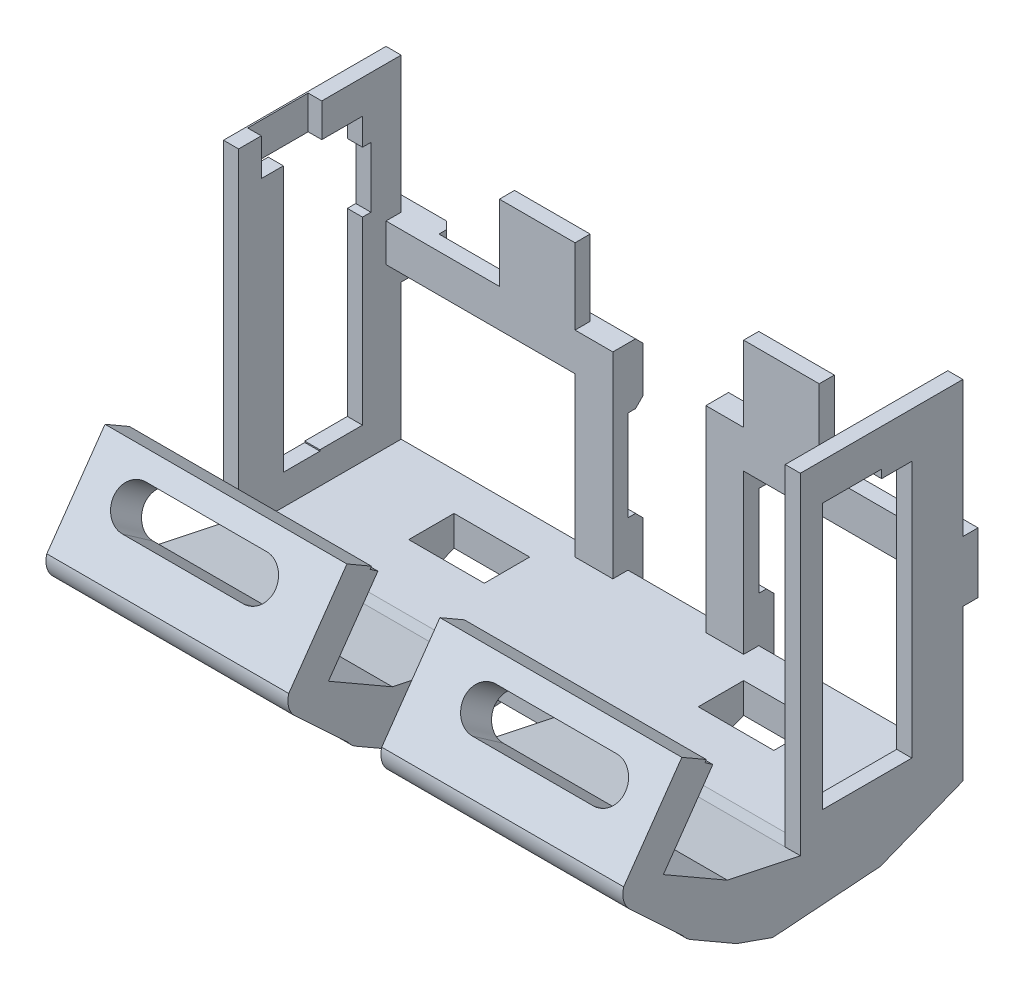
SolidWorks part; units mm, degrees
ref_plane "前视基准面" through (0, 0, 0) normal (0, 0, 1) x (1, 0, 0)
ref_plane "上视基准面" through (0, 0, 0) normal (0, 1, 0) x (1, 0, 0)
ref_plane "右视基准面" through (0, 0, 0) normal (1, 0, 0) x (0, 0, -1)
other "Configuration Table"
sketch "草图5" plane through (0, 0, 0) normal (0, 0, 1) x (1, 0, 0)
  line L0 (-38.15, -23) -> (-38.15, 23)
  line L1 (36.15, -21) -> (-36.15, -21)
  line L2 (36.15, -21) -> (36.15, 23)
  line L4 (-36.15, -21) -> (-36.15, 23)
  line L8 (38.15, -23) -> (38.15, 23)
  line L9 (38.15, -23) -> (-38.15, -23)
  line L10 (36.15, 21) -> (-36.15, 21) construction
  line L11 (38.15, 23) -> (-38.15, 23) construction
  line L12 (-38.15, 23) -> (-36.15, 23)
  line L13 (-36.15, -21) -> (-36.15, 21) construction
  line L14 (36.15, -21) -> (36.15, 21) construction
  line L15 (36.15, 23) -> (38.15, 23)
  point P0 (0, 0)
  dimension "D1" = 72.3
  dimension "D2" = 44
  dimension "D4" = 21
  dimension "D5" = 36.15
  dimension "D3" = 2
extrude "凸台-拉伸2" add sketch "草图5" along normal blind 10
sketch "草图6" plane through (0, 0, 0) normal (0, 0, -1) x (-1, 0, 0)
  line L0 (-38.15, -23) -> (-38.15, 23) construction
  line L1 (-36.15, 5) -> (-6.15, 5)
  line L2 (-38.15, 5) -> (-38.15, 0)
  line L3 (-36.15, 0) -> (-11.15, 0)
  line L5 (38.15, -23) -> (-38.15, -23) construction
  line L7 (-11.15, 0) -> (-11.15, -21)
  line L8 (-11.15, -23) -> (-6.15, -23)
  line L9 (-6.15, 5) -> (-6.15, -21)
  line L10 (38.15, 23) -> (38.15, -23) construction
  line L12 (6.15, 5) -> (6.15, -21)
  line L13 (11.15, 0) -> (36.15, 0)
  line L14 (38.15, 5) -> (38.15, 0)
  line L15 (36.15, -21) -> (36.15, 23) construction
  line L17 (6.15, 5) -> (6.15, 0)
  line L18 (6.15, -23) -> (11.15, -23)
  line L19 (11.15, 0) -> (11.15, -21)
  line L20 (-36.15, 23) -> (-36.15, -21) construction
  line L21 (6.15, 5) -> (38.15, 5)
  line L22 (-36.15, 5) -> (-36.15, 23)
  line L23 (-11.15, -21) -> (-36.15, -21)
  line L24 (6.15, -21) -> (-6.15, -21)
  line L25 (36.15, 0) -> (36.15, -21)
  line L30 (-36.15, -21) -> (-36.15, 23)
  line L31 (-36.15, 23) -> (-38.15, 23)
  line L32 (-38.15, 23) -> (-38.15, -23)
  line L33 (-38.15, -23) -> (38.15, -23)
  line L34 (38.15, -23) -> (38.15, 23)
  line L35 (38.15, 23) -> (36.15, 23)
  line L36 (36.15, 23) -> (36.15, -21)
  line L37 (36.15, -21) -> (-36.15, -21)
  line L38 (-36.15, -21) -> (-36.15, 0)
  line L39 (-36.15, 23) -> (-38.15, 23)
  line L40 (-38.15, 23) -> (-38.15, -23)
  line L41 (-38.15, -23) -> (38.15, -23)
  line L42 (38.15, -23) -> (38.15, 23)
  line L43 (38.15, 23) -> (36.15, 23)
  line L44 (36.15, 23) -> (36.15, 5)
  line L45 (36.15, -21) -> (11.15, -21)
  line M20 (-36.15, -21) -> (-36.15, 23)
  line M21 (-36.15, 23) -> (-38.15, 23)
  line M22 (-38.15, 23) -> (-38.15, -23)
  line M23 (-38.15, -23) -> (38.15, -23)
  line M24 (38.15, -23) -> (38.15, 23)
  line M25 (38.15, 23) -> (36.15, 23)
  line M26 (36.15, 23) -> (36.15, -21)
  line M27 (36.15, -21) -> (-36.15, -21)
  dimension "D1" = 5
  dimension "D2" = 30
  dimension "D3" = 30
  dimension "D4" = 5
  dimension "D5" = 5
  dimension "D7" = 21
  dimension "D6" = 0
extrude "凸台-拉伸3" add sketch "草图6" along normal blind 2 contours L9 L1 L3 L7 M20 M27 | L21 M26 M27 M20 M21 M22 M23 M24 | L21 L12 L19 L13 M27 M26 | L21 M26 M24 M25
sketch "草图7" plane through (0, 0, 10) normal (0, 0, 1) x (1, 0, 0)
  line L8 (36.15, 23) -> (36.15, -21)
  line L9 (36.15, -21) -> (-36.15, -21)
  line L10 (-36.15, -21) -> (-36.15, 23)
  line L11 (-36.15, 23) -> (-38.15, 23)
  line L12 (-38.15, 23) -> (-38.15, -23)
  line L13 (-38.15, -23) -> (38.15, -23)
  line L14 (38.15, -23) -> (38.15, 23)
  line L15 (38.15, 23) -> (36.15, 23)
  line L16 (36.15, 23) -> (36.15, -21)
  line L17 (36.15, -21) -> (-36.15, -21)
  line L18 (-36.15, -21) -> (-36.15, 23)
  line L19 (-36.15, 23) -> (-38.15, 23)
  line L20 (-38.15, 23) -> (-38.15, -23)
  line L21 (-38.15, -23) -> (38.15, -23)
  line L22 (38.15, -23) -> (38.15, 23)
  line L23 (38.15, 23) -> (36.15, 23)
  dimension "D1" = 0
extrude "凸台-拉伸4" add sketch "草图7" along normal blind 9.5
sketch "草图8" plane through (38.15, 0, 0) normal (1, 0, 0) x (0, 0, -1)
  line L0 (-19.5, 23) -> (2, 23) construction
  line L1 (-8.75, 23) -> (-1.75, 23)
  line L2 (-8.75, 14) -> (-8.75, -14)
  line L3 (-8.75, -14) -> (-1.75, -14)
  line L4 (-1.75, 14) -> (-1.75, -14)
  line L5 (-19.5, -23) -> (2, -23) construction
  line L6 (-8.75, 14) -> (-1.75, 14)
  dimension "D1" = 9
  dimension "D2" = 7
  dimension "D3" = 9
  dimension "D4" = 1.75
extrude "切除-拉伸3" cut sketch "草图8" against normal blind 25.5 contours L6 L2 L3 L4
sketch "草图9" plane through (-38.15, 0, 0) normal (-1, 0, 0) x (0, 0, 1)
  line L0 (19.5, 23) -> (19.5, -23) construction
  line L1 (9.5, 15) -> (2, 15)
  line L2 (9.5, 15) -> (9.5, 7)
  line L3 (9.5, 7) -> (2, 7)
  line L4 (2, 15) -> (2, 7)
  line L5 (-2, -23) -> (-2, 23) construction
  line L6 (19.5, 23) -> (-2, 23) construction
  dimension "D1" = 10
  dimension "D2" = 4
  dimension "D3" = 8
  dimension "D4" = 16
extrude "切除-拉伸4" cut sketch "草图9" against normal blind 25.5
sketch "草图10" plane through (0, 23, 0) normal (0, 1, 0) x (1, 0, 0)
  line L0 (-36.15, -19.5) -> (-36.15, 2) construction
  line L1 (-36.15, -13.5) -> (-37.65, -13.5)
  line L2 (-36.15, -13.5) -> (-36.15, -10.5)
  line L3 (-36.15, -10.5) -> (-37.65, -10.5)
  line L4 (-37.65, -13.5) -> (-37.65, -10.5)
  line L5 (-36.15, -19.5) -> (-38.15, -19.5) construction
  dimension "D1" = 9
  dimension "D2" = 6
  dimension "D3" = 1.5
extrude "切除-拉伸5" cut sketch "草图10" against normal blind 32
sketch "草图11" plane through (38.15, 0, 0) normal (1, 0, 0) x (0, 0, -1)
  line L0 (-27.9472, -26.6596) -> (-23.1554, -28.3599)
  line L1 (-23.1554, -28.3599) -> (-8.9035, -27.3246)
  line L2 (-36.6075, -21.6596) -> (-27.6075, -6.0711)
  line L3 (-36.6075, -21.6596) -> (-27.9472, -26.6596)
  line L4 (-19.5, -23) -> (-19.5, 23) construction
  line L9 (2, -23) -> (-19.5, -20.8127)
  line L10 (-8.9035, -27.3246) -> (2, -23)
  line L11 (-27.6075, -6.0711) -> (-23.2736, -8.5647)
  line L12 (-23.2736, -8.5647) -> (-29.1535, -18.784)
  line L13 (-29.1535, -18.784) -> (-19.5, -20.8127)
  dimension "D1" = 5
  dimension "D3" = 10
extrude "凸台-拉伸5" add sketch "草图11" against normal blind 32
sketch "草图12" plane through (0, -23, 0) normal (0, -1, 0) x (1, 0, 0)
  line L0 (0, -2) -> (0, 34.4775)
  line L1 (6.15, -2) -> (-38.15, -2) construction
ref_plane "基准面1" through (0, -23, 0) normal (0, -1, 0) x (0, 0, 1)
ref_plane "基准面2" through (0, 0, 0) normal (1, 0, 0) x (0, 0, 1)
mirror "镜向1" about plane through (0, 0, 0) normal (1, 0, 0) of "凸台-拉伸5"
fillet "圆角1" radius 3 1 edges at (-22.15, -21.6596, 36.6075)
fillet "圆角2" radius 3 1 edges at (22.15, -21.6596, 36.6075)
sketch "草图15" plane through (0, 5, 0) normal (0, 1, 0) x (1, 0, 0)
  line L0 (-11.15, 2) -> (-11.15, 0)
  line L1 (-6.15, 2) -> (-6.15, 0) construction
  line L2 (-21.15, 0) -> (-21.15, 2)
  line L3 (-36.15, 2) -> (-36.15, 0) construction
  line L4 (-36.15, 0) -> (-6.15, 0)
  line L5 (-6.15, 0) -> (-6.15, 2)
  line L6 (-6.15, 2) -> (-36.15, 2)
  line L7 (-36.15, 2) -> (-36.15, 0)
  line L8 (-21.15, 0) -> (-11.15, 0)
  line L10 (-11.15, 2) -> (-21.15, 2)
  line L12 (6.15, 0) -> (36.15, 0)
  line L13 (36.15, 0) -> (36.15, 2)
  line L14 (36.15, 2) -> (6.15, 2)
  line L15 (6.15, 2) -> (6.15, 0)
  line L16 (11.15, 0) -> (21.15, 0)
  line L18 (21.15, 2) -> (11.15, 2)
  line L20 (21.15, 2) -> (21.15, 0)
  line L21 (6.15, 2) -> (6.15, 0) construction
  line L22 (11.15, 0) -> (11.15, 2)
  line L23 (36.15, 2) -> (36.15, 0) construction
  dimension "D3" = 5
  dimension "D4" = 15
  dimension "D5" = 5
  dimension "D6" = 15
  dimension "D1" = 0
  dimension "D2" = 0
extrude "凸台-拉伸6" add sketch "草图15" along normal blind 10
sketch "草图16" plane through (38.15, 0, 0) normal (1, 0, 0) x (0, 0, -1)
  line L0 (-1.75, 5) -> (-1.75, 5.2773)
  line L1 (-1.75, 17) -> (-9.75, 17)
  line L2 (-1.75, 17) -> (-1.75, 5)
  line L3 (-1.75, 5) -> (-9.75, 5)
  line L4 (-9.75, 17) -> (-9.75, 5)
  line L5 (-1.75, 14) -> (-1.75, -14) construction
  line L6 (-8.75, 14) -> (-1.75, 14) construction
  line M15 (-8.75, 14) -> (-1.75, 14)
  line M18 (-8.75, -14) -> (-8.75, 14)
  dimension "D1" = 8
  dimension "D2" = 12
  dimension "D3" = 3
extrude "切除-拉伸7" cut sketch "草图16" against normal blind 10 contours L1 L4 L3 L2 M18 M15
sketch "草图17" plane through (0, -21, 0) normal (0, 1, 0) x (1, 0, 0)
  line L0 (-36.15, -10.5) -> (-36.15, 2) construction
  line L1 (-24.15, -9) -> (-19.15, -9)
  line L2 (-24.15, -9) -> (-24.15, -3)
  line L3 (-24.15, -3) -> (-19.15, -3)
  line L4 (-19.15, -9) -> (-19.15, -3)
  line L5 (-24.15, -9) -> (-19.15, -3) construction
  line L6 (-24.15, -3) -> (-19.15, -9) construction
  line L7 (-21.15, 0) -> (-36.15, 0) construction
  point P0 (-21.65, -6)
  dimension "D1" = 12
  dimension "D2" = 5
  dimension "D3" = 3
  dimension "D4" = 6
extrude "切除-拉伸8" cut sketch "草图17" against normal blind 10
mirror "镜向3" about plane through (0, 0, 0) normal (1, 0, 0) of "切除-拉伸8"
sketch "草图18" plane through (0, 23, 0) normal (0, 1, 0) x (1, 0, 0)
  line L6 (-36.15, -13.5) -> (-37.6541, -13.5)
  line L7 (-36.15, -13.5) -> (-36.15, -16.5)
  line L8 (-36.15, -16.5) -> (-37.6541, -16.5)
  line L9 (-37.6541, -13.5) -> (-37.6541, -16.5)
  dimension "D1" = 3
  dimension "D2" = 1.5041
extrude "切除-拉伸9" cut sketch "草图18" against normal blind 32
sketch "草图19" plane through (0, -21, 0) normal (0, 1, 0) x (1, 0, 0)
  line L0 (-24.15, -9) -> (-19.15, -9) construction
  line L1 (-19.15, -3) -> (-14.15, -3)
  line L2 (-19.15, -3) -> (-19.15, -9)
  line L3 (-19.15, -9) -> (-14.15, -9)
  line L4 (-14.15, -3) -> (-14.15, -9)
  dimension "D1" = 5
extrude "切除-拉伸10" cut sketch "草图19" against normal blind 10
mirror "镜向4" about plane through (0, 0, 0) normal (1, 0, 0) of "切除-拉伸10"
sketch "草图21" plane through (0, 10.4366, 18.0767) normal (0, 0.5, 0.866) x (1, 0, 0)
  line L0 (-29.15, -26.3115) -> (-14.15, -26.3115) construction
  line L1 (-29.15, -23.5615) -> (-14.15, -23.5615)
  line L2 (-29.15, -29.0615) -> (-14.15, -29.0615)
  line L3 (14.15, -26.3115) -> (29.15, -26.3115) construction
  line L4 (14.15, -23.5615) -> (29.15, -23.5615)
  line L5 (14.15, -29.0615) -> (29.15, -29.0615)
  line L6 (6.15, -19.0615) -> (38.15, -19.0615) construction
  line L7 (38.15, -19.0615) -> (38.15, -34.0615) construction
  line L8 (-38.15, -19.0615) -> (-38.15, -34.0615) construction
  line L9 (-6.15, -19.0615) -> (-38.15, -19.0615) construction
  arc A0 (-29.15, -23.5615) -> (-29.15, -29.0615) centre (-29.15, -26.3115) ccw
  arc A1 (-14.15, -29.0615) -> (-14.15, -23.5615) centre (-14.15, -26.3115) ccw
  arc A2 (14.15, -23.5615) -> (14.15, -29.0615) centre (14.15, -26.3115) ccw
  arc A3 (29.15, -29.0615) -> (29.15, -23.5615) centre (29.15, -26.3115) ccw
  point P2 (-21.65, -26.3115)
  point P7 (21.65, -26.3115)
  dimension "D1" = 5.5
  dimension "D2" = 15
  dimension "D3" = 4.5
  dimension "D4" = 9
  dimension "D5" = 9
  dimension "D6" = 4.5
extrude "切除-拉伸11" cut sketch "草图21" against normal blind 10
sketch "草图22" plane through (0, 23, 0) normal (0, 1, 0) x (1, 0, 0)
  line L0 (-37.6541, -16.5) -> (-36.15, -16.5) construction
  line L1 (-36.15, -16.5) -> (-37.95, -16.5)
  line L2 (-36.15, -16.5) -> (-36.15, -8.5)
  line L3 (-36.15, -8.5) -> (-37.95, -8.5)
  line L4 (-37.95, -16.5) -> (-37.95, -8.5)
  line L5 (-36.15, -10.5) -> (-36.15, 2) construction
  dimension "D1" = 1.8
  dimension "D2" = 0
  dimension "D3" = 8
extrude "切除-拉伸12" cut sketch "草图22" against normal blind 34
sketch "草图23" plane through (38.15, 0, 0) normal (1, 0, 0) x (0, 0, -1)
  line L0 (-1.75, 17) -> (-1.75, -14) construction
  line L2 (-8.75, -14) -> (-8.75, 1)
  line L3 (-8.75, 1) -> (-14.75, 1)
  line L4 (-14.75, -14) -> (-14.75, 1)
  line L5 (-8.75, -14) -> (-1.75, -14)
  line L6 (-14.75, -14) -> (-14.75, -17)
  line L7 (-14.75, -17) -> (-1.75, -17)
  line L8 (-1.75, -14) -> (-1.75, -17)
  dimension "D1" = 6
  dimension "D2" = 15
  dimension "D3" = 0
  dimension "D4" = 3
extrude "切除-拉伸13" cut sketch "草图23" against normal blind 34
sketch "草图24" plane through (0, 0, -2) normal (0, 0, -1) x (-1, 0, 0)
  line L0 (-12.2588, -23) -> (12.2588, -23) construction
  line L7 (6.15, -27.3246) -> (6.15, -23) construction
  line L8 (6.15, -23) -> (11.15, -23)
  line L9 (6.15, -23) -> (6.15, -14.9993)
  line L10 (6.15, -14.9993) -> (11.15, -14.9993)
  line L11 (11.15, -23) -> (11.15, -14.9993)
  line L12 (11.15, 0) -> (11.15, -21) construction
  line L13 (11.15, 0) -> (36.15, 0) construction
  line L14 (6.15, 5) -> (14.15, 5)
  line L15 (6.15, 5) -> (6.15, -3)
  line L16 (11.15, 0) -> (14.15, 0)
  line L17 (14.15, 5) -> (14.15, 0)
  line L18 (21.15, 5) -> (36.15, 5) construction
  line L19 (6.15, 5) -> (11.15, 5)
  line L20 (6.15, 5) -> (6.15, -3)
  line L21 (6.15, -3) -> (11.15, -3)
  line L22 (11.15, 0) -> (11.15, -3)
  line L23 (31.15, 5) -> (38.15, 5)
  line L24 (31.15, 5) -> (31.15, 0)
  line L25 (31.15, 0) -> (36.15, 0)
  line L26 (38.15, 5) -> (38.15, -3)
  line L28 (36.15, 0) -> (36.15, -21) construction
  line L29 (38.15, 5) -> (36.15, 5)
  line L30 (38.15, 5) -> (38.15, -3)
  line L31 (38.15, -3) -> (36.15, -3)
  line L32 (36.15, 0) -> (36.15, -3)
  line M9 (11.15, 0) -> (36.15, 0)
  line M10 (36.15, 0) -> (36.15, -21)
  line M12 (11.15, -21) -> (11.15, 0)
  line M19 (6.15, -23) -> (38.15, -23)
  line M20 (38.15, -23) -> (38.15, 23)
  line M23 (36.15, 5) -> (21.15, 5)
  line M27 (11.15, 5) -> (6.15, 5)
  line M28 (6.15, 5) -> (6.15, -21)
  dimension "D1" = 8
  dimension "D2" = 8
  dimension "D3" = 8
  dimension "D4" = 5
  dimension "D5" = 3
  dimension "D6" = 7
  dimension "D7" = 8.0007
extrude "凸台-拉伸7" add sketch "草图24" along normal blind 2 contours L21 L17 L14 M28 M12 M9 M27 | L11 L10 L9 M19 M12 M28 | L31 L23 L24 M20 M23 M9 M10
mirror "镜向5" about plane through (0, 0, 0) normal (1, 0, 0) of "凸台-拉伸7"
chamfer "倒角1" distance 1 angle 45 10 edges at (-8.65, -14.9993, -4) (8.65, -14.9993, -4) (-31.15, 2.5, -4) (31.15, 2.5, -4) (-14.15, 2.5, -4) (-10.15, 5, -4) (-8.65, -3, -4) (8.65, -3, -4) (10.15, 5, -4) (14.15, 2.5, -4)
sketch "草图25" plane through (0, 10.4366, 18.0767) normal (0, 0.5, 0.866) x (1, 0, 0)
  line L0 (29.15, -23.5615) -> (14.15, -23.5615) construction
  line L1 (-29.15, -29.0615) -> (-14.15, -29.0615) construction
  line L2 (-14.15, -23.5615) -> (-29.15, -23.5615) construction
  line L3 (29.15, -23.5615) -> (14.15, -23.5615)
  line L4 (6.15, -19.0615) -> (6.15, -34.0615)
  line L5 (6.15, -34.0615) -> (38.15, -34.0615)
  line L6 (38.15, -34.0615) -> (38.15, -19.0615)
  line L7 (38.15, -19.0615) -> (6.15, -19.0615)
  line L8 (6.15, -19.0615) -> (6.15, -34.0615)
  line L9 (6.15, -34.0615) -> (38.15, -34.0615)
  line L10 (38.15, -34.0615) -> (38.15, -19.0615)
  line L11 (38.15, -19.0615) -> (6.15, -19.0615)
  line L12 (-38.15, -19.0615) -> (-38.15, -34.0615)
  line L13 (-38.15, -34.0615) -> (-6.15, -34.0615)
  line L14 (-6.15, -34.0615) -> (-6.15, -19.0615)
  line L15 (-6.15, -19.0615) -> (-38.15, -19.0615)
  line L16 (-38.15, -19.0615) -> (-38.15, -34.0615)
  line L17 (-38.15, -34.0615) -> (-6.15, -34.0615)
  line L18 (-6.15, -34.0615) -> (-6.15, -19.0615)
  line L19 (-6.15, -19.0615) -> (-38.15, -19.0615)
  line L20 (-29.15, -29.0615) -> (-14.15, -29.0615)
  line L21 (38.15, -30.8442) -> (38.15, -27.7744)
  line L22 (38.15, -27.7744) -> (36.15, -27.7744)
  line L23 (36.15, -27.7744) -> (6.15, -27.7744)
  line L24 (6.15, -27.7744) -> (6.15, -30.8442)
  line L25 (6.15, -30.8442) -> (38.15, -30.8442)
  line L26 (38.15, -30.8442) -> (38.15, -27.7744)
  line L29 (6.15, -27.7744) -> (6.15, -30.8442)
  line L31 (-14.15, -23.5615) -> (-29.15, -23.5615)
  arc A0 (29.15, -29.0615) -> (29.15, -23.5615) centre (29.15, -26.3115) ccw construction
  arc A1 (14.15, -23.5615) -> (14.15, -29.0615) centre (14.15, -26.3115) ccw construction
  arc A2 (-29.15, -23.5615) -> (-29.15, -29.0615) centre (-29.15, -26.3115) ccw construction
  arc A3 (-14.15, -29.0615) -> (-14.15, -23.5615) centre (-14.15, -26.3115) ccw construction
  arc A4 (29.15, -29.0615) -> (29.15, -23.5615) centre (29.15, -26.3115) ccw
  arc A5 (14.15, -23.5615) -> (14.15, -29.0615) centre (14.15, -26.3115) ccw
  arc A6 (-29.15, -23.5615) -> (-29.15, -29.0615) centre (-29.15, -26.3115) ccw
  arc A7 (-14.15, -29.0615) -> (-14.15, -23.5615) centre (-14.15, -26.3115) ccw
  arc M14 (14.15, -29.0615) -> (14.15, -23.5615) centre (14.15, -26.3115) cw
  line M15 (14.15, -23.5615) -> (29.15, -23.5615)
  arc M16 (29.15, -23.5615) -> (29.15, -29.0615) centre (29.15, -26.3115) cw
  line M17 (29.15, -29.0615) -> (14.15, -29.0615)
  line M18 (6.15, -19.0615) -> (6.15, -34.0615)
  line M19 (6.15, -34.0615) -> (38.15, -34.0615)
  line M20 (38.15, -34.0615) -> (38.15, -19.0615)
  line M21 (38.15, -19.0615) -> (6.15, -19.0615)
  dimension "D1" = 0
  dimension "D2" = 0
  dimension "D3" = 0
extrude "凸台-拉伸8" add sketch "草图25" along normal blind 10 contours L18 L19 L16 L17 A7 L20 A6 L31 | L8 L10 M21 M18 M19 M20 M17 M14 M15 M16
sketch "草图26" plane through (38.15, 0, 0) normal (1, 0, 0) x (0, 0, -1)
  line L0 (-34.0094, -23.1596) -> (-43.7677, -14.0615)
  line L1 (-43.7677, -14.0615) -> (-35.1075, -19.0615) construction
  line L2 (-43.7677, -14.0615) -> (-35.1075, -19.0615)
  arc A0 (-35.1075, -19.0615) -> (-34.0094, -23.1596) centre (-32.5094, -20.5615) ccw construction
  arc A1 (-35.1075, -19.0615) -> (-34.0094, -23.1596) centre (-32.5094, -20.5615) ccw
  line M5 (-43.7677, -14.0615) -> (-35.1075, -19.0615)
  arc M6 (-35.1075, -19.0615) -> (-34.0094, -23.1596) centre (-32.5094, -20.5615) ccw
extrude "凸台-拉伸9" add sketch "草图26" against normal blind 32 contours L0 M6 M5
mirror "镜向7" about plane through (0, 0, 0) normal (1, 0, 0) of "凸台-拉伸9"
sketch "草图27" plane through (0, 7.9303, 13.7829) normal (0, -0.4987, -0.8668) x (-1, 0, 0)
  line L3 (6.15, -30.8206) -> (38.15, -30.8206) construction
  line L4 (-38.15, -19.0305) -> (-38.15, -30.8206) construction
  line L5 (-38.15, -30.8206) -> (-6.15, -30.8206) construction
  line L11 (6.15, -30.8206) -> (38.15, -30.8206)
  line L12 (-38.15, -19.0305) -> (-38.15, -30.8206)
  line L13 (-38.15, -30.8206) -> (-6.15, -30.8206)
  line L17 (-38.15, -30.8206) -> (42.1742, -30.8206)
  line L18 (-38.15, -30.8206) -> (-38.15, -16.5611)
  line L19 (-38.15, -16.5611) -> (42.1742, -16.5611)
  line L20 (42.1742, -30.8206) -> (42.1742, -16.5611)
  line M7 (-6.15, -30.8206) -> (-6.15, -19.0305)
  line M8 (-6.15, -19.0305) -> (-38.15, -19.0305)
extrude "切除-拉伸15" cut sketch "草图27" against normal blind 10 contours L17 L20 L19 L18 L11 M8 M7
mirror "镜向8" about plane through (0, 0, 0) normal (1, 0, 0) of "切除-拉伸15"
fillet "圆角3" radius 3 2 edges at (-22.15, -14.0615, 43.7677) (22.15, -14.0615, 43.7677)
sketch "草图28" plane through (-38.15, 0, 0) normal (-1, 0, 0) x (0, 0, 1)
  line L1 (3.1141, 18.5575) -> (15.3403, 18.5575)
  line L2 (3.1141, 18.5575) -> (3.1141, -16.8342)
  line L3 (3.1141, -16.8342) -> (15.3403, -16.8342)
  line L4 (15.3403, 18.5575) -> (15.3403, -16.8342)
extrude "切除-拉伸16" cut sketch "草图28" against normal blind 10
sketch "草图29" plane through (38.15, 0, 0) normal (1, 0, 0) x (0, 0, -1)
  line L1 (-42.8676, -12.6942) -> (-35.172, -1.7037)
  line L20 (-36.2677, -1.0711) -> (-42.5745, -11.9947)
  line L21 (-42.0222, -15.689) -> (-34.9962, -22.2396)
  line L22 (-34.0094, -23.1596) -> (-27.9472, -26.6596)
  line L23 (-27.9472, -26.6596) -> (-23.1554, -28.3599)
  line L24 (-23.1554, -28.3599) -> (-8.9035, -27.3246)
  line L25 (-8.9035, -27.3246) -> (2, -23)
  line L26 (2, -23) -> (2, -3)
  line L27 (2, -3) -> (4, -3)
  line L28 (4, -3) -> (4, 5)
  line L29 (4, 5) -> (2, 5)
  line L30 (2, 5) -> (2, 23)
  line L31 (2, 23) -> (-19.5, 23)
  line L32 (-19.5, 23) -> (-19.5, -20.8127)
  line L33 (-19.5, -20.8127) -> (-29.1535, -18.784)
  line L34 (-29.1535, -18.784) -> (-37.8212, -13.7969)
  line L35 (-37.8212, -13.7969) -> (-31.9376, -3.5711)
  line L36 (-31.9376, -3.5711) -> (-36.2677, -1.0711)
  line L37 (-36.2677, -1.0711) -> (-42.5745, -11.9947)
  line L53 (-35.172, -1.7037) -> (-36.2677, -1.0711)
  arc A2 (-42.5745, -11.9947) -> (-42.0222, -15.689) centre (-39.9764, -13.4947) ccw
  arc A3 (-34.9962, -22.2396) -> (-34.0094, -23.1596) centre (-32.5094, -20.5615) ccw
  arc A4 (-42.5745, -11.9947) -> (-42.8676, -12.6942) centre (-39.9764, -13.4947) ccw
  dimension "D2" = 0
extrude "切除-拉伸17" cut sketch "草图29" against normal blind 95
sketch "草图30" plane through (38.15, 0, 0) normal (1, 0, 0) x (0, 0, -1)
  line L1 (-14.75, -17) -> (-16.5781, -17)
  line L3 (-14.75, 18.1031) -> (-16.5781, 18.1031)
  line L4 (-16.5781, -17) -> (-16.5781, 18.1031)
  line L5 (-14.75, -17) -> (-8.75, -17)
  line L7 (-14.75, 18.1031) -> (-8.75, 18.1031)
  line L8 (-8.75, -17) -> (-8.75, 18.1031)
  dimension "D1" = 6
extrude "切除-拉伸18" cut sketch "草图30" against normal blind 95
sketch "草图31" plane through (38.15, 0, 0) normal (1, 0, 0) x (0, 0, -1)
  line L0 (-16.5781, -17) -> (-1.75, -17) construction
  line L1 (-1.75, 17) -> (-4.75, 17)
  line L2 (-1.75, 17) -> (-1.75, -17)
  line L3 (-1.75, -17) -> (-4.75, -17)
  line L4 (-4.75, 17) -> (-4.75, -17)
  dimension "D1" = 3
extrude "凸台-拉伸10" add sketch "草图31" against normal blind 2
sketch "草图32" plane through (-38.15, 0, 0) normal (-1, 0, 0) x (0, 0, 1)
  line L0 (16.5781, -17) -> (8.75, -17) construction
  line L1 (16.5781, 18.1031) -> (13.5781, 18.1031)
  line L2 (16.5781, 18.1031) -> (16.5781, -17)
  line L3 (16.5781, -17) -> (13.5781, -17)
  line L4 (13.5781, 18.1031) -> (13.5781, -17)
  dimension "D1" = 3
extrude "凸台-拉伸11" add sketch "草图32" against normal blind 2
sketch "草图33" plane through (0, 15.9649, 22.8003) normal (0, 0.5736, 0.8192) x (1, 0, 0)
  line L1 (38.15, -21.5695) -> (6.15, -21.5695)
  line L2 (38.15, -21.5695) -> (38.15, -34.9863)
  line L3 (38.15, -34.9863) -> (6.15, -34.9863)
  line L4 (6.15, -21.5695) -> (6.15, -34.9863)
  line L5 (-6.15, -21.5695) -> (-38.15, -21.5695)
  line L6 (-6.15, -21.5695) -> (-6.15, -34.9863)
  line L7 (-6.15, -34.9863) -> (-38.15, -34.9863)
  line L8 (-38.15, -21.5695) -> (-38.15, -34.9863)
extrude "凸台-拉伸12" add sketch "草图33" against normal blind 5
sketch "草图34" plane through (0, 15.9649, 22.8003) normal (0, 0.5736, 0.8192) x (1, 0, 0)
  line L0 (-31.15, -27.0695) -> (-15.15, -27.0695) construction
  line L1 (-31.15, -24.3695) -> (-15.15, -24.3695)
  line L2 (-31.15, -29.7695) -> (-15.15, -29.7695)
  line L3 (-38.15, -21.5695) -> (-6.15, -21.5695) construction
  line L4 (-6.15, -21.5695) -> (-6.15, -34.9863) construction
  arc A0 (-31.15, -24.3695) -> (-31.15, -29.7695) centre (-31.15, -27.0695) ccw
  arc A1 (-15.15, -29.7695) -> (-15.15, -24.3695) centre (-15.15, -27.0695) ccw
  point P2 (-23.15, -27.0695)
  dimension "D3" = 16
  dimension "D1" = 5.5
  dimension "D2" = 5.4
  dimension "D4" = 9
extrude "切除-拉伸19" cut sketch "草图34" against normal blind 5
mirror "镜向9" about plane through (0, 0, 0) normal (1, 0, 0) of "切除-拉伸19"
